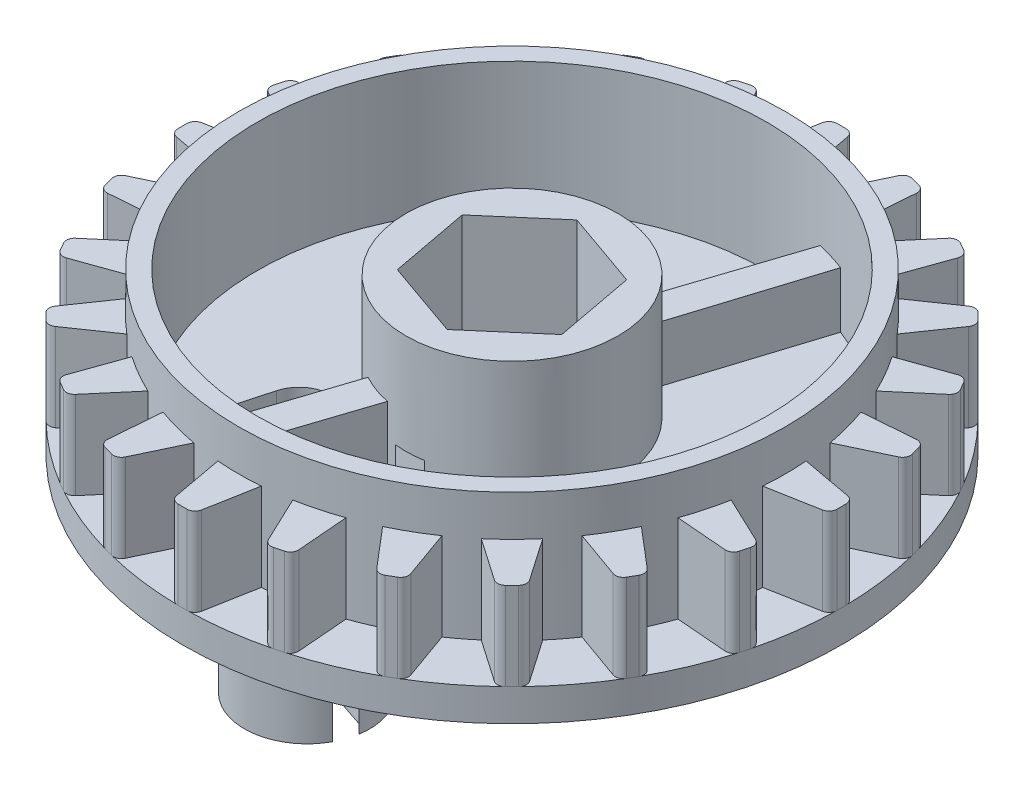
SolidWorks part; units mm, degrees
ref_plane "Front Plane" through (0, 0, 0) normal (0, 0, 1) x (1, 0, 0)
ref_plane "Top Plane" through (0, 0, 0) normal (0, 1, 0) x (1, 0, 0)
ref_plane "Right Plane" through (0, 0, 0) normal (1, 0, 0) x (0, 0, -1)
sketch "Sketch2" plane through (0, 0, 0) normal (0, 1, 0) x (1, 0, 0)
  circle A0 centre (0, 0) radius 10.25
  dimension "D1" = 20.5
extrude "Boss-Extrude3" add sketch "Sketch2" along normal blind 1
sketch "Sketch3" plane through (0, 1, 0) normal (0, 1, 0) x (1, 0, 0)
  circle A0 centre (0, 0) radius 8.5
  circle A1 centre (0, 0) radius 7.925
  dimension "D1" = 17
  dimension "D2" = 15.85
extrude "Boss-Extrude4" add sketch "Sketch3" along normal blind 4
sketch "Sketch4" plane through (0, 1, 0) normal (0, 1, 0) x (1, 0, 0)
  circle A0 centre (0, 0) radius 3.3
  dimension "D1" = 6.6
extrude "Boss-Extrude6" add sketch "Sketch4" along normal blind 3.85
sketch "Sketch5" plane through (0, 0, 0) normal (0, -1, 0) x (1, 0, 0)
  line L1 (0.4674, 2.4852) -> (-1.9185, 1.6474)
  line L2 (-1.9185, 1.6474) -> (-2.386, -0.8378)
  line L3 (-2.386, -0.8378) -> (-0.4674, -2.4852)
  line L4 (-0.4674, -2.4852) -> (1.9185, -1.6474)
  line L5 (1.9185, -1.6474) -> (2.386, 0.8378)
  line L6 (2.386, 0.8378) -> (0.4674, 2.4852)
  circle A0 centre (0, 0) radius 2.19 construction
extrude "Cut-Extrude5" cut sketch "Sketch5" against normal through all
sketch "Sketch9" plane through (0, 1, 0) normal (0, 1, 0) x (1, 0, 0)
  line L0 (0, 0) -> (0, 13.7934) construction
  line L1 (0.68, 8.45) -> (-0.68, 8.45)
  line L2 (-0.68, 8.45) -> (-0.3876, 10.0451)
  line L3 (-0.1417, 10.25) -> (0.1417, 10.25)
  line L4 (0.3876, 10.0451) -> (0.68, 8.45)
  arc A0 (0.1417, 10.25) -> (0.3876, 10.0451) centre (0.1417, 10) cw
  arc A1 (-0.3876, 10.0451) -> (-0.1417, 10.25) centre (-0.1417, 10) cw
  point P5 (0, 0)
  point P8 (0, 0)
  point P9 (0, 0)
  point P12 (0.35, 10.25)
  point P15 (-0.35, 10.25)
  dimension "D5" = 0.25
  dimension "D1" = 1.36
  dimension "D2" = 0.7
  dimension "D3" = 8.45
  dimension "D4" = 10.25
extrude "Boss-Extrude9" add sketch "Sketch9" along normal blind 2.73
pattern_circular "CirPattern1" count 24 every 15 about axis through (0, 0, 0) along (0, 1, 0) of "Boss-Extrude9"
sketch "Sketch13" plane through (0, 0, 0) normal (0, -1, 0) x (-1, 0, 0)
  line L0 (1.6565, -4.7176) -> (-4.1414, -6.7635) construction
  line L1 (-4.1414, -6.7635) -> (6.9543, -2.8482) construction
  line L2 (0.2836, -5.7104) -> (3.4284, -4.6539)
  line L3 (-0.1596, -5.4901) -> (-0.2552, -5.2057)
  line L4 (3.5858, -4.3373) -> (3.4265, -3.8633)
  line L5 (-0.0348, -4.7625) -> (3.1099, -3.706)
  circle A0 centre (1.6565, -4.7176) radius 1.95
  circle A2 centre (1.6565, -4.7176) radius 0.9
  arc A3 (3.4284, -4.6539) -> (3.5858, -4.3373) centre (3.3488, -4.4169) ccw
  arc A4 (3.4265, -3.8633) -> (3.1099, -3.706) centre (3.1895, -3.943) ccw
  arc A5 (-0.1596, -5.4901) -> (0.2836, -5.7104) centre (0.1722, -5.3787) ccw
  arc A6 (-0.2552, -5.2057) -> (-0.0348, -4.7625) centre (0.0766, -5.0943) cw
  point P12 (3.6654, -4.5743)
  point P15 (3.3469, -3.6264)
  dimension "D1" = 3.9
  dimension "D2" = 1.8
  dimension "D5" = 0.25
  dimension "D6" = 0.35
  dimension "D3" = 5
  dimension "D4" = 1
extrude "Boss-Extrude17" add sketch "Sketch13" along normal blind 4.88 contours A0 A6 L5 A2 A4 | A5 A0 A3 L2 A2
sketch "Sketch16" plane through (0, 0, 0) normal (0, -1, 0) x (1, 0, 0)
  line L0 (-2.2474, 6.5759) -> (-4.2053, 6.0357)
  line L1 (-4.9032, 4.8057) -> (-4.3867, 2.9337)
  line L2 (-3.1567, 2.2357) -> (0.7891, 3.3245)
  line L3 (1.4871, 4.5544) -> (0.9705, 6.4265)
  line L4 (-0.2595, 7.1245) -> (-2.2474, 6.5759)
  arc A0 (0.0624, 5.6385) -> (-3.5916, 4.4765) centre (-1.6565, 4.7176) ccw construction
  arc A1 (0.9705, 6.4265) -> (-0.2595, 7.1245) centre (0.0065, 6.1605) ccw
  arc A2 (0.7891, 3.3245) -> (1.4871, 4.5544) centre (0.5231, 4.2885) ccw
  arc A3 (-4.3867, 2.9337) -> (-3.1567, 2.2357) centre (-3.4227, 3.1997) ccw
  arc A4 (-4.2053, 6.0357) -> (-4.9032, 4.8057) centre (-3.9393, 5.0717) ccw
  circle A5 centre (-1.6565, 4.7176) radius 1.95
  point P14 (-4.1207, 1.9697)
  point P17 (-5.1692, 5.7697)
  point P21 (0, 0)
  dimension "D2" = 1
  dimension "D1" = 3.8
extrude "Cut-Extrude27" cut sketch "Sketch16" against normal blind 1.74
sketch "Sketch17" plane through (0, 1, 0) normal (0, 1, 0) x (1, 0, 0)
  line L0 (0.4396, 1.6466) -> (-3.7527, -11.0819)
  line L1 (-2.5717, -7.4961) -> (-3.0445, -7.3169)
  line L2 (-3.0445, -7.3169) -> (-1.5605, -2.8114)
  line L3 (-1.5605, -2.8114) -> (-0.5998, -3.1279)
  line L4 (-0.5998, -3.1279) -> (-2.0838, -7.6333)
  line L5 (-2.0838, -7.6333) -> (-2.5717, -7.4961)
  circle A0 centre (0, 0) radius 7.925 construction
  point P4 (-1.6565, -4.7176)
extrude "Boss-Extrude21" add sketch "Sketch17" along normal blind 1.74
sketch "Sketch18" plane through (0, 1, 0) normal (0, 1, 0) x (1, 0, 0)
  line L0 (-0.8247, -3.8107) -> (15640.8199, 47486.5984)
  line L2 (2.8095, 7.4103) -> (1.3703, 2.8537)
  line L3 (-2.0295, -4.2355) -> (15639.615, 47486.1736)
  line L4 (1.3703, 2.8537) -> (0.382, 3.0864)
  line L5 (0.382, 3.0864) -> (1.8996, 7.694)
  line L6 (2.8095, 7.4103) -> (2.8095, 7.694)
  line L7 (2.8095, 7.694) -> (2.0411, 7.9419)
  line L8 (2.0411, 7.9419) -> (1.8996, 7.694)
  arc A0 (-2.5717, -7.4961) -> (-3.0445, -7.3169) centre (0, 0) ccw construction
extrude "Boss-Extrude25" add sketch "Sketch18" along normal blind 1.74
